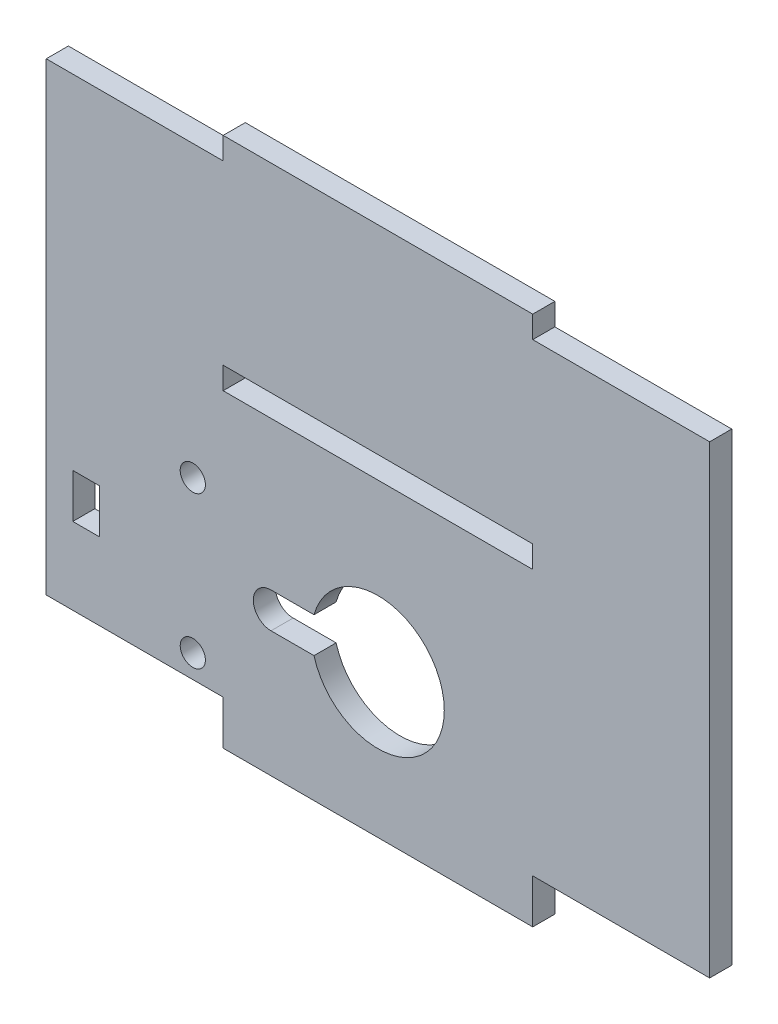
SolidWorks part; units mm, degrees
material "Beech"
ref_plane "Front" through (0, 0, 0) normal (0, 0, 1) x (1, 0, 0)
ref_plane "Top" through (0, 0, 0) normal (0, 1, 0) x (1, 0, 0)
ref_plane "Right" through (0, 0, 0) normal (1, 0, 0) x (0, 0, -1)
sketch "Sketch1" plane through (0, 0, 0) normal (0, 0, 1) x (1, 0, 0)
  line L1 (-37.5, -30) -> (37.5, -30) construction
  line L2 (-37.5, -30) -> (-37.5, 30) construction
  line L3 (-37.5, 30) -> (37.5, 30) construction
  line L4 (37.5, -30) -> (37.5, 30) construction
  line L5 (-37.5, -30) -> (37.5, 30) construction
  line L6 (-37.5, 30) -> (37.5, -30) construction
  line L12 (-6.6223, 0) -> (6.869, 0) construction
  line L13 (0, -5.4827) -> (0, 10.2112) construction
  line L24 (-12.09, -13.8) -> (-22.5996, -13.8) construction
  line L25 (-12.09, -11.8) -> (-7.2284, -11.8)
  line L26 (-12.09, -15.8) -> (-7.2284, -15.8)
  line L27 (1.7695, -13.8) -> (-19.9118, -13.8) construction
  line L41 (-34.5, -16.3) -> (-31.5, -16.3)
  line L42 (-34.5, -16.3) -> (-34.5, -11.3)
  line L43 (-34.5, -11.3) -> (-31.5, -11.3)
  line L44 (-31.5, -16.3) -> (-31.5, -11.3)
  line L45 (-34.5, -16.3) -> (-31.5, -11.3) construction
  line L46 (-34.5, -11.3) -> (-31.5, -16.3) construction
  line L58 (17.5, 30) -> (-17.5, 30)
  line L59 (-17.5, 30) -> (-17.5, 27.5)
  line L60 (-17.5, 27.5) -> (-37.5, 27.5)
  line L61 (-37.5, 27.5) -> (-37.5, -25)
  line L62 (-37.5, -25) -> (-17.5, -25)
  line L63 (-17.5, -25) -> (-17.5, -30)
  line L64 (-17.5, -30) -> (17.5, -30)
  line L65 (17.5, -25) -> (17.5, -30)
  line L66 (37.5, -25) -> (17.5, -25)
  line L67 (37.5, 27.5) -> (37.5, -25)
  line L68 (17.5, 27.5) -> (37.5, 27.5)
  line L69 (17.5, 30) -> (17.5, 27.5)
  line L71 (-17.5, 5) -> (17.5, 5)
  line L72 (-17.5, 5) -> (-17.5, 7.5)
  line L73 (-17.5, 7.5) -> (17.5, 7.5)
  line L74 (17.5, 5) -> (17.5, 7.5)
  line L75 (-17.5, 5) -> (17.5, 7.5) construction
  line L76 (-17.5, 7.5) -> (17.5, 5) construction
  arc A0 (-7.2284, -15.8) -> (-7.2284, -11.8) centre (0, -13.8) ccw
  arc A1 (-12.09, -11.8) -> (-12.09, -15.8) centre (-12.09, -13.8) ccw
  circle A3 centre (-20.93, -5.22) radius 1.425
  circle A4 centre (-20.93, -22.38) radius 1.425
  point P0 (0, 0)
  point P6 (0, 6.25)
  point P24 (0, -42.5)
  point P26 (0, 30)
  point P32 (-33, -13.8)
  point P34 (37.5, 0)
  point P36 (0, 30)
  point P43 (-33, -11.3)
  point P45 (0, -30)
  point P53 (-37.5, 0)
  point P55 (0, 30)
  dimension "D8" = 15
  dimension "D11" = 2.85
  dimension "D1" = 75
  dimension "D2" = 60
  dimension "D3" = 2.5
  dimension "D4" = 20
  dimension "D5" = 30
  dimension "D6" = 4
  dimension "D7" = 11.2
  dimension "D9" = 12.09
  dimension "D10" = 8.58
  dimension "D12" = 20.93
  dimension "D13" = 3
  dimension "D14" = 5
  dimension "D15" = 33
  dimension "D16" = 5
extrude "Boss-Extrude1" add sketch "Sketch1" along normal blind 2.5
